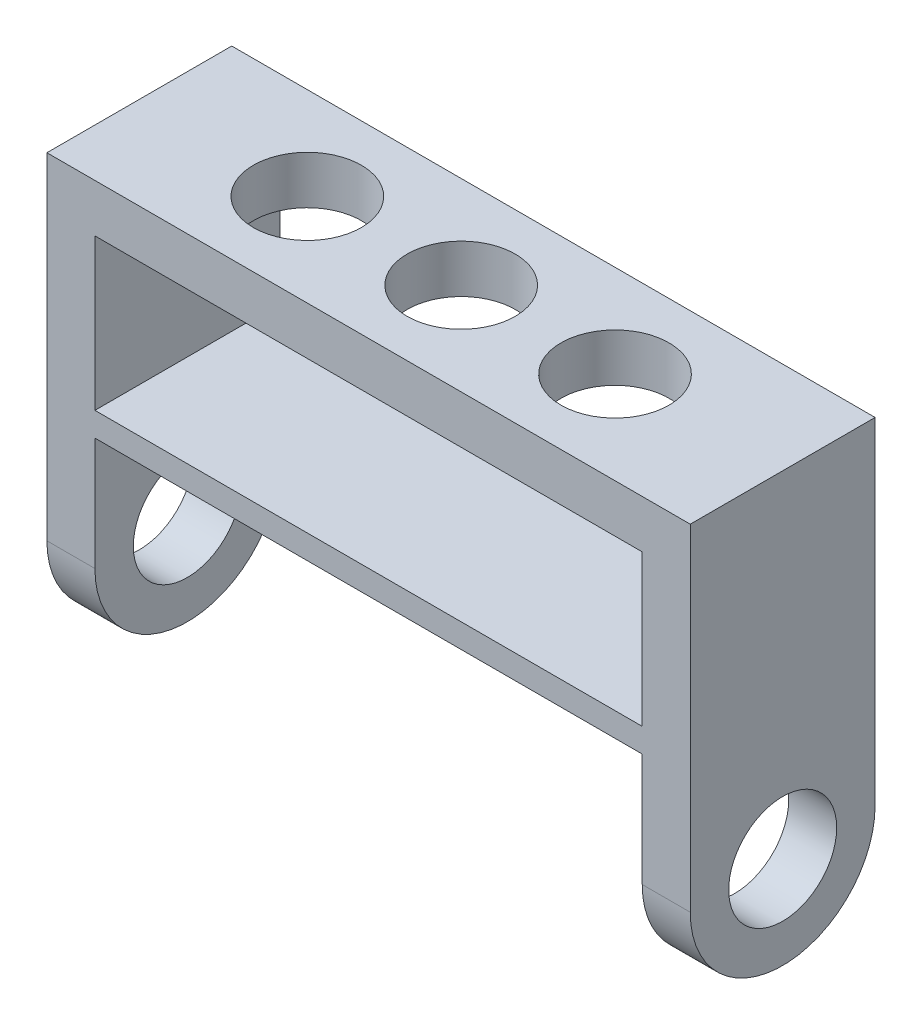
SolidWorks part; units mm, degrees
ref_plane "Front Plane" through (0, 0, 0) normal (0, 0, 1) x (1, 0, 0)
ref_plane "Top Plane" through (0, 0, 0) normal (0, 1, 0) x (1, 0, 0)
ref_plane "Right Plane" through (0, 0, 0) normal (1, 0, 0) x (0, 0, -1)
sketch "Sketch1" plane through (0, 0, 0) normal (1, 0, 0) x (0, 0, -1)
  line L0 (-24.4475, 0) -> (-24.4475, 88.9)
  line L1 (24.4475, 0) -> (24.4475, 88.9)
  line L2 (24.4475, 88.9) -> (-24.4475, 88.9)
  circle A0 centre (0, 0) radius 14.2875
  arc A1 (-24.4475, 0) -> (24.4475, 0) centre (0, 0) ccw
  dimension "D1" = 28.575
  dimension "D2" = 10.16
  dimension "D3" = 88.9
extrude "Boss-Extrude1" add sketch "Sketch1" along normal blind 12.7
sketch "Sketch2" plane through (0, 0, 0) normal (-1, 0, 0) x (0, 0, 1)
  line L0 (-24.4475, 0) -> (-24.4475, 88.9) construction
  line L1 (-24.4475, 29.8819) -> (24.4475, 29.8819)
  line L2 (-24.4475, 29.8819) -> (-24.4475, 36.2319)
  line L3 (-24.4475, 36.2319) -> (24.4475, 36.2319)
  line L4 (24.4475, 29.8819) -> (24.4475, 36.2319)
  line L5 (24.4475, 88.9) -> (24.4475, 0) construction
  line L7 (-24.4475, 88.9) -> (24.4475, 88.9)
  line L8 (-24.4475, 88.9) -> (-24.4475, 76.2)
  line L9 (-24.4475, 76.2) -> (24.4475, 76.2)
  line L10 (24.4475, 88.9) -> (24.4475, 76.2)
  dimension "D1" = 6.35
  dimension "D2" = 12.7
extrude "Boss-Extrude2" add sketch "Sketch2" along normal blind 144.78
sketch "Sketch3" plane through (-144.78, 0, 0) normal (-1, 0, 0) x (0, 0, 1)
  line L0 (-24.4475, 0) -> (-24.4475, 88.9)
  line L1 (-24.4475, 88.9) -> (24.4475, 88.9)
  line L2 (24.4475, 88.9) -> (24.4475, 0)
  circle A0 centre (0, 0) radius 14.2875
  arc A1 (-24.4475, 0) -> (24.4475, 0) centre (0, 0) ccw
extrude "Boss-Extrude3" add sketch "Sketch3" along normal blind 12.7
sketch "Sketch4" plane through (0, 88.9, 0) normal (0, 1, 0) x (1, 0, 0)
  line L0 (-157.48, -24.4475) -> (-157.48, 24.4475) construction
  circle A0 centre (-113.03, 0) radius 14.2875
  circle A1 centre (-72.3392, 0) radius 14.2875
  circle A2 centre (-31.6484, 0) radius 14.2875
  dimension "D1" = 28.575
  dimension "D2" = 28.575
  dimension "D3" = 40.6908
  dimension "D5" = 28.575
  dimension "D6" = 40.6908
  dimension "D4" = 44.45
extrude "Cut-Extrude1" cut sketch "Sketch4" against normal blind 25.654
